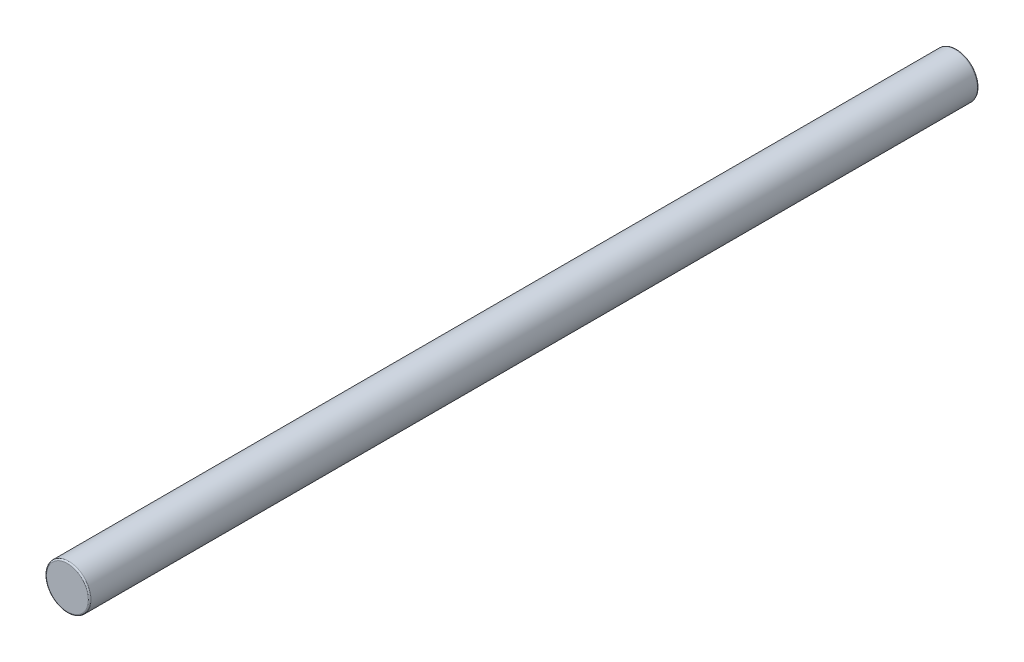
SolidWorks part; units mm, degrees
ref_plane "Płaszczyzna przednia" through (0, 0, 0) normal (0, 0, 1) x (1, 0, 0)
ref_plane "Płaszczyzna górna" through (0, 0, 0) normal (0, 1, 0) x (1, 0, 0)
ref_plane "Płaszczyzna prawa" through (0, 0, 0) normal (1, 0, 0) x (0, 0, -1)
sketch "Szkic1" plane through (0, 0, 0) normal (0, 0, 1) x (1, 0, 0)
  circle A0 centre (0, 0) radius 5
  dimension "D1" = 10
extrude "Dodanie-wyciągnięcie1" add sketch "Szkic1" along normal mid plane 200
fillet "Zaokrąglenie1" radius 0.3 2 edges at (5, 0, -100) (5, 0, 100)
